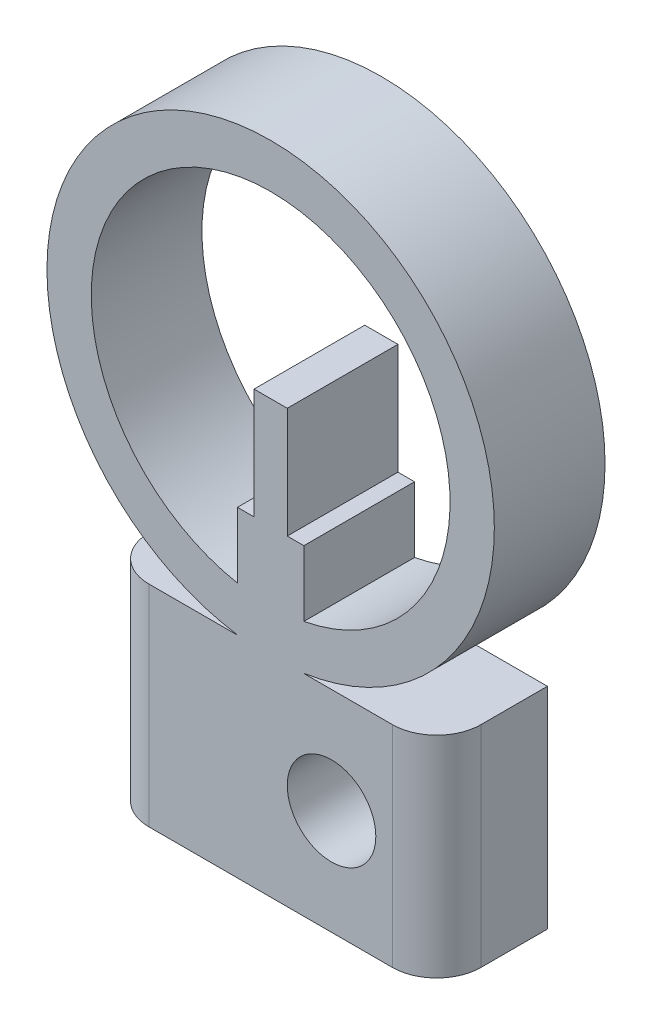
SolidWorks part; units mm, degrees
ref_plane "Front Plane" through (0, 0, 0) normal (0, 0, 1) x (1, 0, 0)
ref_plane "Top Plane" through (0, 0, 0) normal (0, 1, 0) x (1, 0, 0)
ref_plane "Right Plane" through (0, 0, 0) normal (1, 0, 0) x (0, 0, -1)
sketch "Sketch1" plane through (0, 0, 0) normal (0, 0, 1) x (1, 0, 0)
  line L0 (7.5, 4.75) -> (-2, 4.75) construction
  line L1 (7.5, 4.75) -> (-7.5, 4.75)
  line L2 (7.5, 4.75) -> (7.5, -4.75)
  line L3 (7.5, -4.75) -> (-7.5, -4.75)
  line L4 (-7.5, 4.75) -> (-7.5, -4.75)
  line L5 (7.5, 4.75) -> (-7.5, -4.75) construction
  line L6 (7.5, -4.75) -> (-7.5, 4.75) construction
  point P0 (0, 0)
  dimension "D1" = 9.5
  dimension "D2" = 15
extrude "Boss-Extrude2" add sketch "Sketch1" against normal blind 5 contours L2 L1 L4 L3
sketch "Sketch3" plane through (0, 0, 0) normal (0, 0, 1) x (1, 0, 0)
  line L0 (7.5, 4.75) -> (-2, 4.75) construction
  line L1 (7.5, 4.75) -> (-7.5, 4.75) construction
  line L2 (7.5, 4.75) -> (7.5, -4.75) construction
  line L3 (-2, 4.75) -> (7.5, -4.75) construction
  circle A0 centre (2.75, 0) radius 2
  dimension "D1" = 4
extrude "Cut-Extrude1" cut sketch "Sketch3" against normal through all both and the other way through all
sketch "Sketch4" plane through (0, 4.75, 0) normal (0, 1, 0) x (1, 0, 0)
  line L0 (0, 5) -> (0, 0) construction
  line L1 (7.5, 5) -> (-7.5, 5) construction
  line L2 (7.5, 0) -> (-7.5, 0) construction
  line L4 (1.5, 5) -> (-1.5, 5)
  line L5 (1.5, 5) -> (1.5, 0)
  line L6 (1.5, 0) -> (-1.5, 0)
  line L7 (-1.5, 5) -> (-1.5, 0)
  line L8 (1.5, 5) -> (-1.5, 0) construction
  line L9 (1.5, 0) -> (-1.5, 5) construction
  point P6 (0, 2.5)
  dimension "D1" = 3
extrude "Boss-Extrude3" add sketch "Sketch4" along normal blind 5
fillet "Fillet1" radius 2 2 edges at (-7.5, 0, 0) (7.5, 0, 0)
sketch "Sketch5" plane through (0, 0, 0) normal (0, 0, 1) x (1, 0, 0)
  line L0 (-0.75, 9.75) -> (0.75, 9.75)
  line L1 (-1.5, 9.75) -> (1.5, 9.75) construction
  line L2 (0, 9.75) -> (0, 3.4492) construction
  line L3 (0, 9.75) -> (-0.75, 9.75)
  line L4 (-0.75, 9.75) -> (-0.75, 14.75)
  line L7 (0.75, 9.75) -> (0.75, 14.75)
  line L8 (0.75, 14.75) -> (-0.75, 14.75)
  point P0 (0, 0)
  dimension "D1" = 1.5
  dimension "D2" = 5
  dimension "D3" = 0.75
extrude "Boss-Extrude4" add sketch "Sketch5" against normal up to vertex (5 mm away) contours L0 L7 L8 L4
sketch "Sketch6" plane through (0, 0, 0) normal (0, 0, 1) x (1, 0, 0)
  line L0 (0.75, 14.75) -> (-0.75, 14.75) construction
  circle A0 centre (0, 14.75) radius 10.1033
  circle A1 centre (0, 14.75) radius 8.1033
  dimension "D1" = 2
extrude "Boss-Extrude5" add sketch "Sketch6" against normal blind 5
